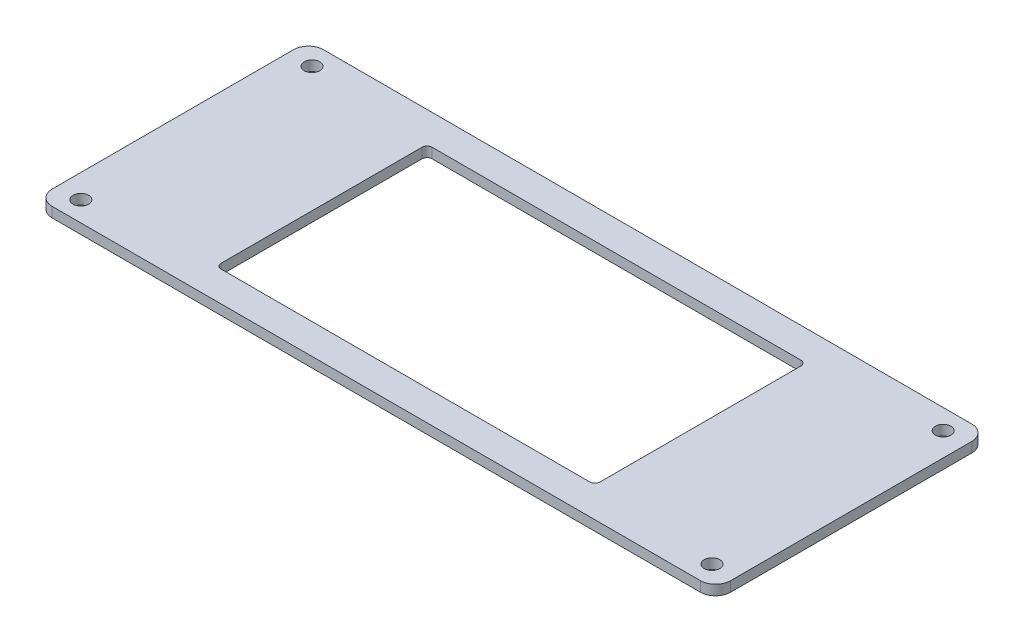
SolidWorks part; units mm, degrees
material "VMA 碳纤维"
ref_plane "前视基准面" through (0, 0, 0) normal (0, 0, 1) x (1, 0, 0)
ref_plane "上视基准面" through (0, 0, 0) normal (0, 1, 0) x (1, 0, 0)
ref_plane "右视基准面" through (0, 0, 0) normal (1, 0, 0) x (0, 0, -1)
other "Configuration Table"
sketch "草图1" plane through (0, 0, 0) normal (0, 1, 0) x (1, 0, 0)
  line L0 (-59.5, -27) -> (-62.5, -27)
  line L1 (-59.5, -27) -> (59.5, -27)
  line L2 (-62.5, -24) -> (-62.5, 24)
  line L3 (-59.5, 27) -> (59.5, 27)
  line L4 (62.5, -24) -> (62.5, 24)
  line L5 (-62.5, -27) -> (62.5, 27) construction
  line L6 (-62.5, 27) -> (62.5, -27) construction
  line L7 (-41.9, 21) -> (31.5, 21)
  line L8 (-42.9, 20) -> (-42.9, -20)
  line L9 (-41.9, -21) -> (31.5, -21)
  line L10 (32.5, 20) -> (32.5, -20)
  line L11 (-62.5, -27) -> (-62.5, -24)
  line L12 (-59.5, 27) -> (-62.5, 27)
  line L13 (-62.5, 27) -> (-62.5, 24)
  arc A0 (59.5, 27) -> (62.5, 24) centre (59.5, 24) cw
  arc A1 (59.5, -27) -> (62.5, -24) centre (59.5, -24) ccw
  arc A2 (-59.5, -27) -> (-62.5, -24) centre (-59.5, -24) cw construction
  arc A3 (-62.5, 24) -> (-59.5, 27) centre (-59.5, 24) cw construction
  arc A4 (31.5, -21) -> (32.5, -20) centre (31.5, -20) ccw
  arc A5 (31.5, 21) -> (32.5, 20) centre (31.5, 20) cw
  arc A6 (-41.9, 21) -> (-42.9, 20) centre (-41.9, 20) ccw
  arc A7 (-42.9, -20) -> (-41.9, -21) centre (-41.9, -20) ccw
  point P0 (0, 0)
  point P24 (32.5, -21)
  point P29 (-42.9, 21)
  point P32 (-42.9, -21)
  dimension "D7" = 3
  dimension "D8" = 1
  dimension "D1" = 125
  dimension "D2" = 75.4
  dimension "D3" = 42
  dimension "D4" = 6
  dimension "D5" = 6
  dimension "D6" = 19.6
extrude "凸台-拉伸1" add sketch "草图1" along normal blind 2
sketch "草图3" plane through (0, 2, 0) normal (0, 1, 0) x (1, 0, 0)
  line L0 (-62.5, -27) -> (59.5, -27) construction
  line L1 (-62.5, 27) -> (-72.5, 27)
  line L2 (-62.5, 27) -> (-62.5, -27)
  line L3 (-62.5, -27) -> (-72.5, -27)
  line L4 (-72.5, 27) -> (-72.5, -27)
  dimension "D1" = 10
extrude "凸台-拉伸2" add sketch "草图3" against normal up to surface (2 mm away) up to face at (20.0404, 0, 0)
sketch "草图2" plane through (0, 2, 0) normal (0, 1, 0) x (1, 0, 0)
  line L0 (-81.6458, 0) -> (0, 0) construction
  line L1 (0, 0) -> (0, -54.2706) construction
  line L3 (-72.5, -27) -> (59.5, -27) construction
  circle A0 centre (-57.8, -23) radius 1.55 construction
  circle A1 centre (-57.8, 23) radius 1.55 construction
  circle A2 centre (57.8, 23) radius 1.55
  circle A3 centre (57.8, -23) radius 1.55
  circle A4 centre (-67.8, -23) radius 1.55
  circle A5 centre (-67.8, 23) radius 1.55
  dimension "D3" = 3.1
  dimension "D1" = 115.6
  dimension "D2" = 4
  dimension "D5" = 10
  dimension "D4" = 2
extrude "切除-拉伸1" cut sketch "草图2" against normal blind 2
fillet "圆角1" radius 3 2 edges at (-72.5, 1, 27) (-72.5, 1, -27)
